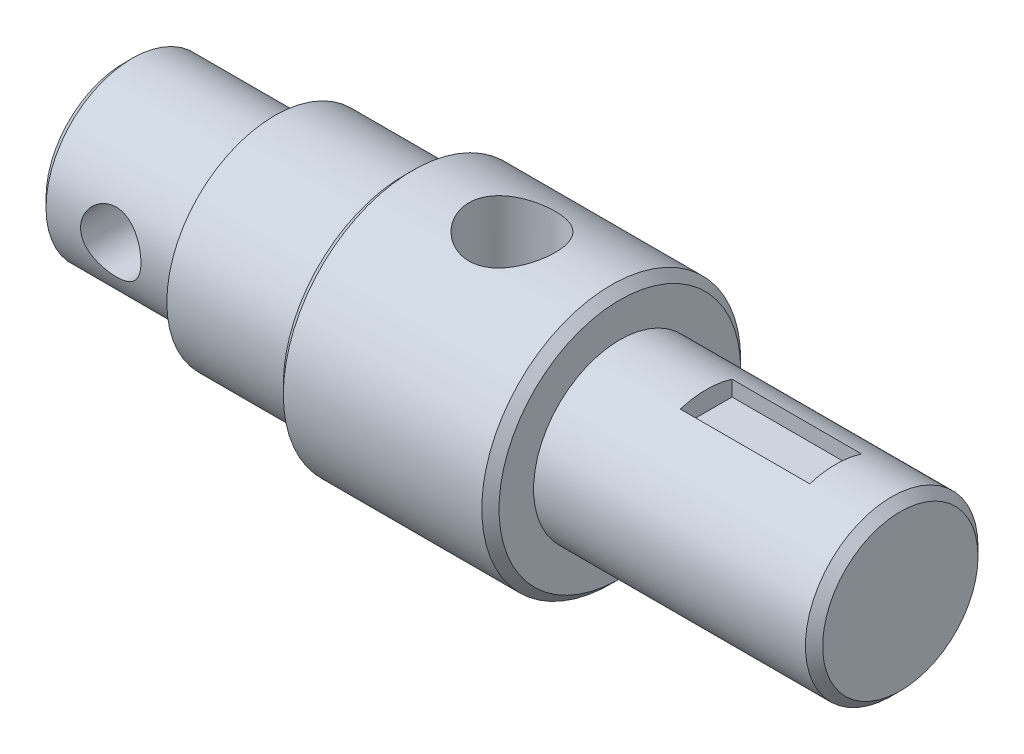
SolidWorks part; units mm, degrees
ref_plane "Спереди" through (0, 0, 0) normal (0, 0, 1) x (1, 0, 0)
ref_plane "Сверху" through (0, 0, 0) normal (0, 1, 0) x (1, 0, 0)
ref_plane "Справа" through (0, 0, 0) normal (1, 0, 0) x (0, 0, -1)
sketch "Эскиз1" plane through (0, 0, 0) normal (0, 0, 1) x (1, 0, 0)
  line L0 (0, 0) -> (-42.8669, 0) construction
  line L1 (0, 0) -> (0, 20)
  line L2 (0, 20) -> (35, 20)
  line L3 (35, 20) -> (35, 25)
  line L4 (35, 25) -> (65, 25)
  line L5 (65, 25) -> (65, 30)
  line L6 (65, 30) -> (115, 30)
  line L7 (115, 30) -> (115, 20)
  line L8 (115, 20) -> (180, 20)
  line L9 (180, 20) -> (180, 0)
  line L10 (180, 0) -> (0, 0)
  dimension "D1" = 40
  dimension "D2" = 50
  dimension "D3" = 60
  dimension "D4" = 180
  dimension "D5" = 35
  dimension "D6" = 65
  dimension "D7" = 50
revolve "Повернуть1" add sketch "Эскиз1" angle 360 about L0
sketch "Эскиз2" plane through (0, 0, 0) normal (0, 0, 1) x (1, 0, 0)
  line L0 (180, 20) -> (115, 20) construction
  line L1 (135, 20) -> (165, 20)
  line L2 (135, 20) -> (135, 15.5)
  line L3 (135, 15.5) -> (165, 15.5)
  line L4 (165, 20) -> (165, 15.5)
  line L5 (180, -20) -> (180, 20) construction
  dimension "D1" = 30
  dimension "D2" = 15
  dimension "D3" = 4.5
extrude "Вырез-Вытянуть1" cut sketch "Эскиз2" against normal mid plane 12
sketch "Эскиз3" plane through (0, 0, 0) normal (0, 0, 1) x (1, 0, 0)
  line L0 (0, 0) -> (35, 0) construction
  line L1 (35, 20) -> (35, -20) construction
  line L2 (0, 20) -> (0, -20) construction
  circle A0 centre (17, 0) radius 7
  dimension "D1" = 14
  dimension "D2" = 17
extrude "Вырез-Вытянуть2" cut sketch "Эскиз3" against normal through all both and the other way through all
ref_plane "Плоскость4" through (0, 30, 0) normal (0, 1, 0) x (1, 0, 0)
hole_wizard "Диаметр отверстия Ø16.0 (20)1" positions "Эскиз5" profile "Эскиз4" hole size "Ø16.0" standard "ISO"
sketch "Эскиз5" plane through (0, 30, 0) normal (0, 1, 0) x (1, 0, 0)
  line L0 (65, 30) -> (65, -30) construction
  line L1 (65, 0) -> (115, 0) construction
  line L2 (115, -20) -> (115, 20) construction
  point P0 (90, 0)
  dimension "D1" = 25
sketch "Эскиз4" plane through (90, 30, 0) normal (1, 0, 0) x (0, 0, 1)
  line L0 (0, 0) -> (0, 26.0086)
  line L1 (0, 26.0086) -> (10, 20)
  line L2 (10, 20) -> (10, 0)
  line L5 (10, 0) -> (0, 0)
  line L10 (0, 26.0086) -> (-10, 20) construction
  line L11 (0, -6.35) -> (0, 107.95) construction
  dimension "Диаметр отверстия" = 20
  dimension "Глубина отверстия" = 20
  dimension "Угол заточки сверла" = 118
pattern_circular "Круговой массив1" count 2 over 360 about axis through (0, 0, 0) along (1, 0, 0) of "Диаметр отверстия Ø16.0 (20)1"
chamfer "Фаска1" distance 2 angle 45 4 edges at (180, 0, -20) (115, 0, -30) (65, 0, -30) (0, 0, -20)
